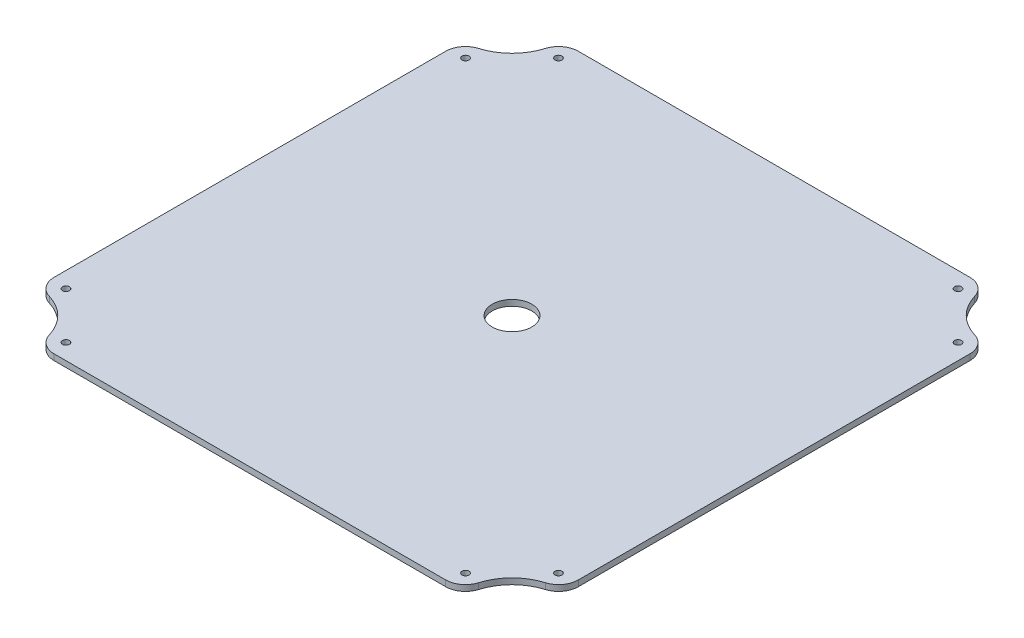
SolidWorks part; units mm, degrees
ref_plane "前视基准面" through (0, 0, 0) normal (0, 0, 1) x (1, 0, 0)
ref_plane "上视基准面" through (0, 0, 0) normal (0, 1, 0) x (1, 0, 0)
ref_plane "右视基准面" through (0, 0, 0) normal (1, 0, 0) x (0, 0, -1)
sketch "草图2" plane through (0, 0, 0) normal (0, 1, 0) x (1, 0, 0)
  line L1 (-132.5, -132.5) -> (132.5, -132.5)
  line L2 (-132.5, -132.5) -> (-132.5, 132.5)
  line L3 (-132.5, 132.5) -> (132.5, 132.5)
  line L4 (132.5, -132.5) -> (132.5, 132.5)
  line L7 (-132.5, 132.5) -> (132.5, -132.5) construction
  line L8 (132.5, 132.5) -> (-132.5, -132.5) construction
  circle A2 centre (0, 0) radius 10
  dimension "D2" = 20
  dimension "D1" = 265
extrude "黄板" add sketch "草图2" along normal blind 3
sketch "草图3" plane through (0, 3, 0) normal (0, 1, 0) x (1, 0, 0)
  line L0 (-124.5, -101) -> (-132.5, -101) construction
  line L1 (-132.5, -132.5) -> (132.5, -132.5) construction
  line L3 (-132.5, 132.5) -> (132.5, 132.5) construction
  line L4 (132.5, -132.5) -> (132.5, 132.5) construction
  line L5 (-101, -124.5) -> (-101, -132.5) construction
  line L7 (-132.5, -132.5) -> (-132.5, 132.5) construction
  circle A0 centre (-132.5, -132.5) radius 25
  circle A4 centre (-132.5, -132.5) radius 32.5 construction
  circle A6 centre (-132.5, 132.5) radius 25
  circle A8 centre (-124.5, 101) radius 1.75
  circle A10 centre (-101, 124.5) radius 1.75
  circle A11 centre (-124.5, -101) radius 1.75
  circle A12 centre (-101, -124.5) radius 1.75
  circle A13 centre (132.5, 132.5) radius 25
  circle A14 centre (101, 124.5) radius 1.75
  circle A15 centre (124.5, 101) radius 1.75
  circle A16 centre (132.5, -132.5) radius 25
  circle A17 centre (124.5, -101) radius 1.75
  circle A18 centre (101, -124.5) radius 1.75
  point P21 (0, 0)
  point P40 (0, 0)
  dimension "D1" = 50
  dimension "D2" = 65
  dimension "D4" = 3.5
  dimension "D5" = 8
  dimension "D3" = 4
extrude "切除-拉伸2" cut sketch "草图3" against normal through all both and the other way through all
fillet "圆角2" radius 10 8 edges at (132.5, 1.5, -107.5) (132.5, 1.5, 107.5) (107.5, 1.5, 132.5) (-132.5, 1.5, 107.5) (-132.5, 1.5, -107.5) (-107.5, 1.5, -132.5) (107.5, 1.5, -132.5) (-107.5, 1.5, 132.5)
